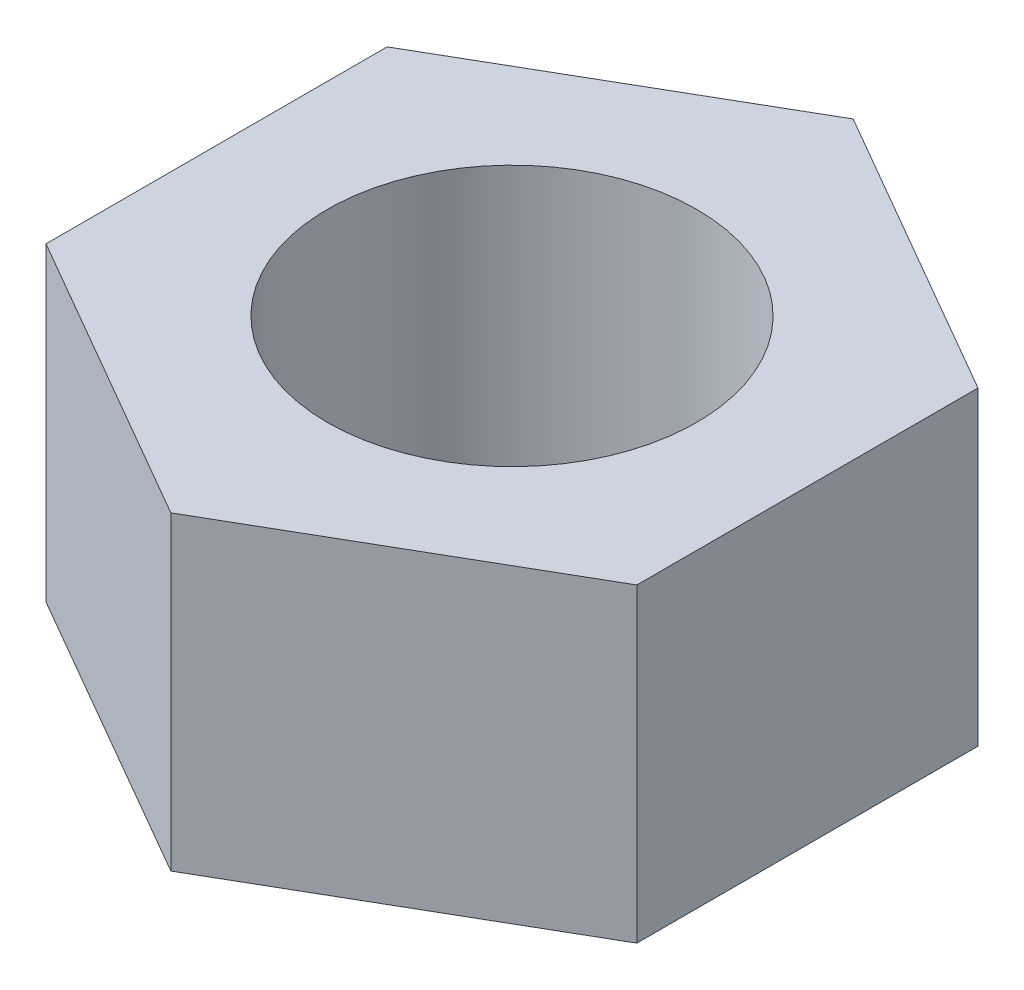
SolidWorks part; units mm, degrees
ref_plane "Front Plane" through (0, 0, 0) normal (0, 0, 1) x (1, 0, 0)
ref_plane "Top Plane" through (0, 0, 0) normal (0, 1, 0) x (1, 0, 0)
ref_plane "Right Plane" through (0, 0, 0) normal (1, 0, 0) x (0, 0, -1)
sketch "Sketch1" plane through (0, 0, 0) normal (0, 1, 0) x (1, 0, 0)
  line L1 (0, 9.2376) -> (-8, 4.6188)
  line L2 (-8, 4.6188) -> (-8, -4.6188)
  line L3 (-8, -4.6188) -> (0, -9.2376)
  line L4 (0, -9.2376) -> (8, -4.6188)
  line L5 (8, -4.6188) -> (8, 4.6188)
  line L6 (8, 4.6188) -> (0, 9.2376)
  circle A0 centre (0, 0) radius 8 construction
extrude "Boss-Extrude1" add sketch "Sketch1" against normal blind 8.4
sketch "Sketch2" plane through (0, 0, 0) normal (0, 1, 0) x (1, 0, 0)
  circle A0 centre (0, 0) radius 5
extrude "Cut-Extrude1" cut sketch "Sketch2" against normal through all
